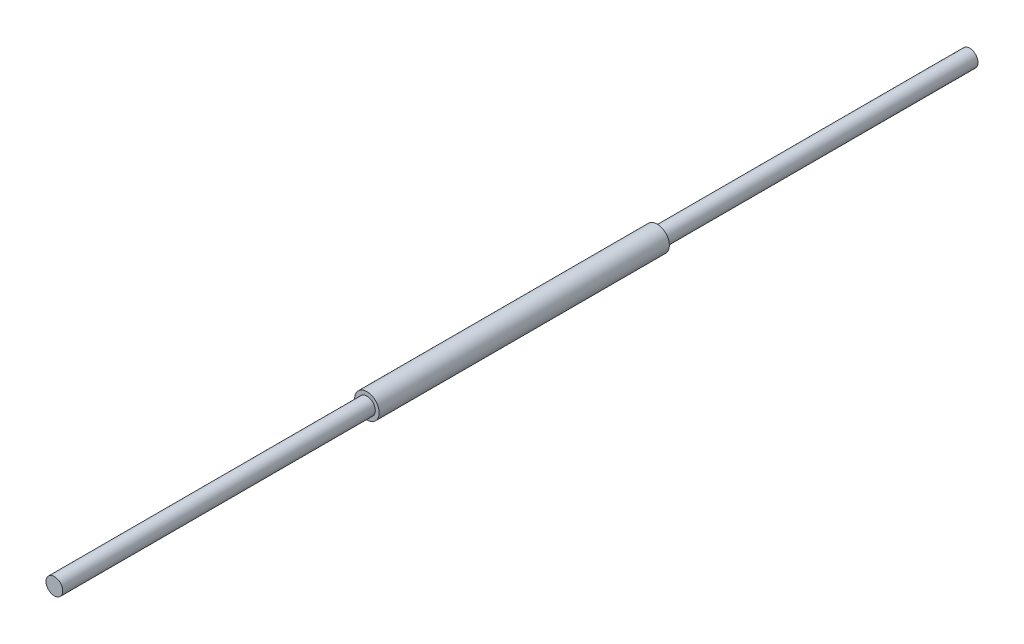
SolidWorks part; units mm, degrees
material "AISI 1020"
ref_plane "Front Plane" through (0, 0, 0) normal (0, 0, 1) x (1, 0, 0)
ref_plane "Top Plane" through (0, 0, 0) normal (0, 1, 0) x (1, 0, 0)
ref_plane "Right Plane" through (0, 0, 0) normal (1, 0, 0) x (0, 0, -1)
sketch "Sketch1" plane through (0, 0, 0) normal (1, 0, 0) x (0, 0, -1)
  line L0 (-282.4761, 0) -> (282.4761, 0) construction
  line L1 (0, 0) -> (0, 133.3095) construction
  line L2 (-82.55, 6.985) -> (82.55, 6.985)
  line L3 (82.55, 6.985) -> (82.55, 4.7625)
  line L4 (82.55, 4.7625) -> (260.35, 4.7625)
  line L5 (260.35, 4.7625) -> (260.35, 0)
  line L6 (-260.35, 4.7625) -> (-260.35, 0)
  line L7 (-82.55, 4.7625) -> (-260.35, 4.7625)
  line L8 (-82.55, 6.985) -> (-82.55, 4.7625)
  line L9 (260.35, 0) -> (-260.35, 0)
  point P3 (82.55, 3.1733)
  point P4 (0, 0)
  point P16 (0, 6.985)
  dimension "D1" = 520.7
  dimension "D2" = 165.1
  dimension "D3" = 13.97
  dimension "D4" = 9.525
revolve "Revolve1" add sketch "Sketch1" angle 360 about L9
equation "\"a\"= 20.5"
equation "\"b\"= 6.5"
equation "\"c\"= 36"
equation "\"D1@Sketch1\"=\"a\""
equation "\"D2@Sketch1\"=\"b\""
